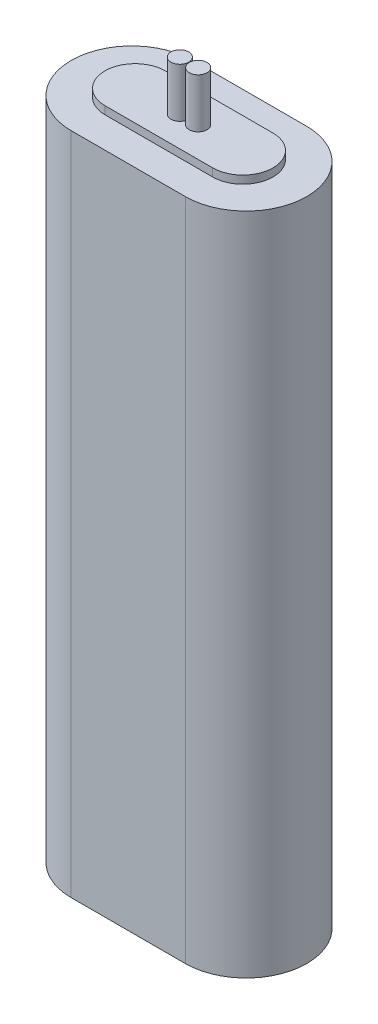
SolidWorks part; units mm, degrees
ref_plane "Plan de face" through (0, 0, 0) normal (0, 0, 1) x (1, 0, 0)
ref_plane "Plan de dessus" through (0, 0, 0) normal (0, 1, 0) x (1, 0, 0)
ref_plane "Plan de droite" through (0, 0, 0) normal (1, 0, 0) x (0, 0, -1)
sketch "Esquisse1" plane through (0, 0, 0) normal (0, 1, 0) x (1, 0, 0)
  line L0 (-11.55, 0) -> (11.55, 0) construction
  line L1 (-11.55, 12.3) -> (11.55, 12.3)
  line L2 (-11.55, -12.3) -> (11.55, -12.3)
  arc A0 (-11.55, 12.3) -> (-11.55, -12.3) centre (-11.55, 0) ccw
  arc A1 (11.55, -12.3) -> (11.55, 12.3) centre (11.55, 0) ccw
  point P2 (0, 0)
  point P8 (23.85, 0)
  point P9 (-23.85, 0)
  dimension "D1" = 47.7
  dimension "D2" = 24.6
extrude "Boss.-Extru.1" add sketch "Esquisse1" along normal mid plane 134.4
sketch "Esquisse2" plane through (0, 67.2, 0) normal (0, 1, 0) x (1, 0, 0)
  line L0 (-10.9, 0) -> (10.9, 0) construction
  line L1 (-10.9, 6.1) -> (10.9, 6.1)
  line L2 (-10.9, -6.1) -> (10.9, -6.1)
  arc A0 (-10.9, 6.1) -> (-10.9, -6.1) centre (-10.9, 0) ccw
  arc A1 (10.9, -6.1) -> (10.9, 6.1) centre (10.9, 0) ccw
  point P2 (0, 0)
  point P8 (17, 0)
  point P9 (-17, 0)
  dimension "D1" = 12.2
  dimension "D2" = 34
extrude "Boss.-Extru.2" add sketch "Esquisse2" along normal blind 1.6
sketch "Esquisse3" plane through (0, 68.8, 0) normal (0, 1, 0) x (1, 0, 0)
  line L0 (0, 0) -> (0, 2.0396) construction
  circle A0 centre (-1.85, 0) radius 1.8
  circle A1 centre (1.85, 0) radius 1.8
  dimension "D1" = 3.6
  dimension "D2" = 3.7
extrude "Boss.-Extru.3" add sketch "Esquisse3" along normal blind 10
